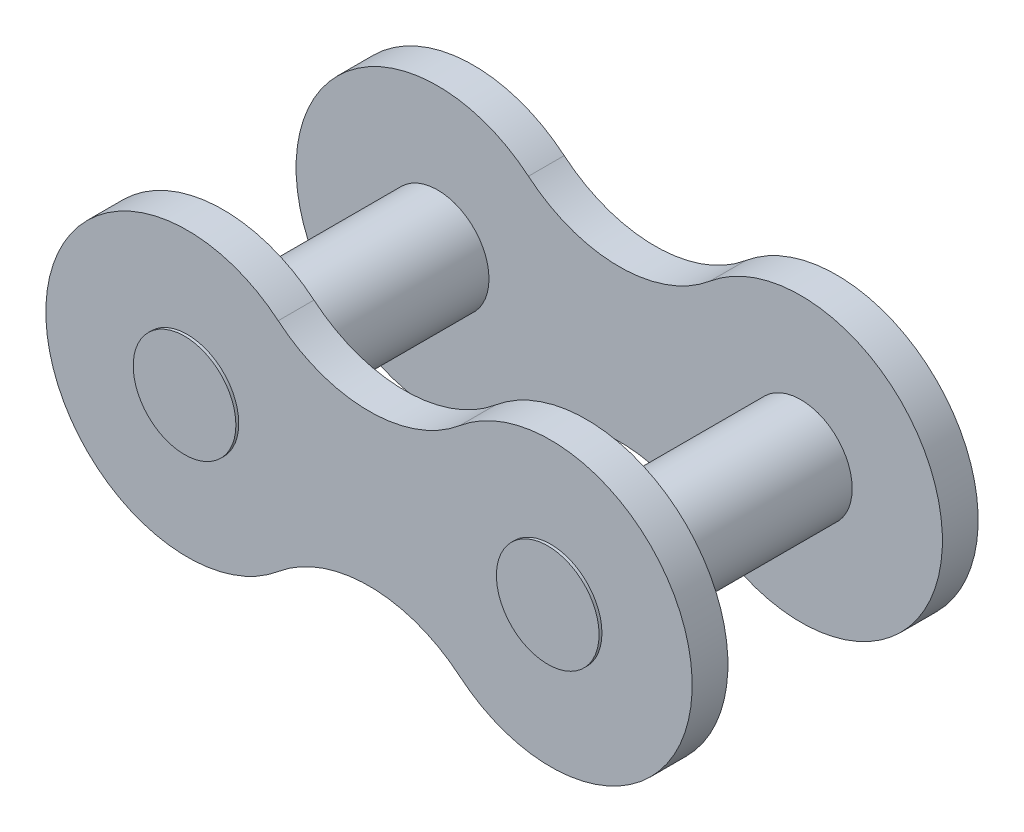
SolidWorks part; units mm, degrees
ref_plane "Спереди" through (0, 0, 0) normal (0, 0, 1) x (1, 0, 0)
ref_plane "Сверху" through (0, 0, 0) normal (0, 1, 0) x (1, 0, 0)
ref_plane "Справа" through (0, 0, 0) normal (1, 0, 0) x (0, 0, -1)
sketch "Эскиз1" plane through (0, 0, 0) normal (0, 0, 1) x (1, 0, 0)
  line L0 (-12.9643, 0) -> (25.4438, 0) construction
  line L1 (0, 0) -> (0, 11.9293) construction
  line L2 (-6.35, -4.9488) -> (15.0678, -4.9488) construction
  arc A0 (3.175, -8.7464) -> (3.175, -1.1512) centre (6.35, -4.9488) ccw
  arc A1 (-3.175, -8.7464) -> (-3.175, -1.1512) centre (-6.35, -4.9488) cw
  arc A2 (-3.175, -1.1512) -> (3.175, -1.1512) centre (0, 2.6465) ccw
  arc A3 (-3.175, -8.7464) -> (3.175, -8.7464) centre (0, -12.544) cw
  circle A4 centre (-6.35, -4.9488) radius 1.795
  circle A5 centre (6.35, -4.9488) radius 1.795
  point P9 (6.2397, 0)
  dimension "D1" = 9.9
  dimension "D3" = 4.95
  dimension "D4" = 3.59
  dimension "D2" = 12.7
ref_plane "Плоскость1" through (0, 0, 5) normal (0, 0, 1) x (1, 0, 0)
sketch "Эскиз2" plane through (0, 0, 5) normal (0, 0, 1) x (1, 0, 0)
  circle A1 centre (6.35, -4.9488) radius 1.795
  circle A2 centre (6.35, -4.9488) radius 1.795
  circle A3 centre (-6.35, -4.9488) radius 1.795
  circle A4 centre (-6.35, -4.9488) radius 1.795
  arc A8 (3.175, -8.7464) -> (3.175, -1.1512) centre (6.35, -4.9488) ccw
  arc A9 (-3.175, -1.1512) -> (3.175, -1.1512) centre (0, 2.6465) ccw
  arc A10 (-3.175, -1.1512) -> (-3.175, -8.7464) centre (-6.35, -4.9488) ccw
  arc A11 (3.175, -8.7464) -> (-3.175, -8.7464) centre (0, -12.544) ccw
  arc A12 (3.175, -8.7464) -> (3.175, -1.1512) centre (6.35, -4.9488) ccw
  arc A13 (-3.175, -1.1512) -> (3.175, -1.1512) centre (0, 2.6465) ccw
  arc A14 (-3.175, -1.1512) -> (-3.175, -8.7464) centre (-6.35, -4.9488) ccw
  arc A15 (3.175, -8.7464) -> (-3.175, -8.7464) centre (0, -12.544) ccw
  dimension "D1" = 0
  dimension "D2" = 0
  dimension "D3" = 0
extrude "Бобышка-Вытянуть1" add sketch "Эскиз2" against normal blind 1.25
mirror "Зеркальное отражение3" about plane through (0, 0, 0) normal (0, 0, 1) of bodies 103
extrude "Бобышка-Вытянуть2" add sketch "Эскиз1" along normal blind 5.1 and the other way blind 5.1 contours A5 | A4
sketch "Sketch1" plane through (0, 0, 0) normal (0, 0, 1) x (1, 0, 0)
  line L0 (-6.35, -4.9488) -> (6.35, -4.9488) construction
equation "\"t shag\"= 12.7'b"
equation "\"b1\"= 3.3"
equation "\"d1\"= 7.75"
equation "\"b2\"= 5.8"
equation "\"d2\"= 3.59"
equation "\"g\"= 9.9"
equation "\"a1\"= 10.2"
equation "\"k\"= 1.5"
equation "\"D1@Эскиз1\"=\"g\""
equation "\"D2@Эскиз1\"=\"t shag\""
equation "\"D3@Эскиз1\"=\"g\"/2"
equation "\"D4@Эскиз1\"=\"d2\""
equation "\"D1@Плоскость1\"= \"a1\" / 2 - 0.1"
equation "\"D1@Бобышка-Вытянуть1\"= ( \"b2\" - \"b1\" ) / 2"
equation "\"D1@Бобышка-Вытянуть2\"= \"a1\" / 2"
equation "\"D2@Бобышка-Вытянуть2\"= \"a1\" / 2"
